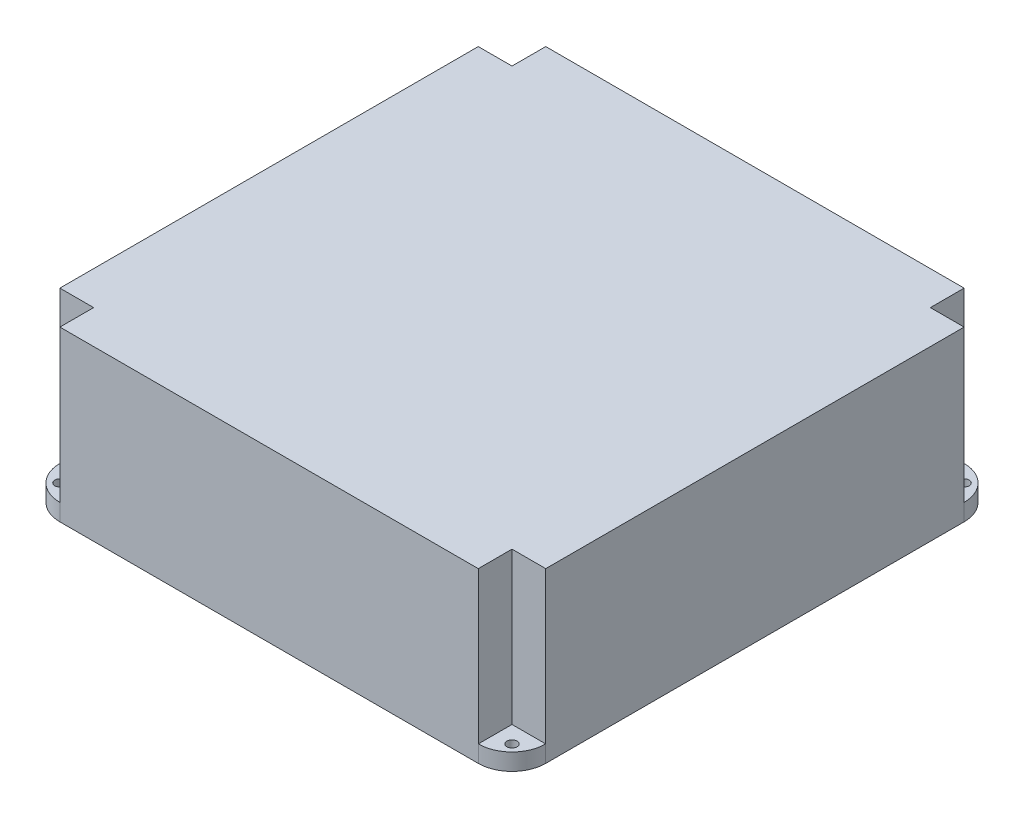
SolidWorks part; units mm, degrees
ref_plane "Front Plane" through (0, 0, 0) normal (0, 0, 1) x (1, 0, 0)
ref_plane "Top Plane" through (0, 0, 0) normal (0, 1, 0) x (1, 0, 0)
ref_plane "Right Plane" through (0, 0, 0) normal (1, 0, 0) x (0, 0, -1)
sketch "Sketch1" plane through (0, 0, 0) normal (0, 1, 0) x (1, 0, 0)
  line L0 (0, 72) -> (0, -72) construction
  line L1 (-62, 72) -> (62, 72)
  line L2 (-72, 62) -> (-72, -62)
  line L3 (-62, -72) -> (62, -72)
  line L5 (-72, 62) -> (-62, 62)
  line L6 (-62, 62) -> (-62, 72)
  line L7 (-72, 0) -> (72, 0) construction
  line L8 (62, 62) -> (62, 72)
  line L9 (72, 62) -> (62, 62)
  line L10 (62, -62) -> (62, -72)
  line L11 (72, -62) -> (62, -62)
  line L12 (-72, -62) -> (-62, -62)
  line L13 (-62, -62) -> (-62, -72)
  line L14 (72, 62) -> (72, -62)
  line L15 (-62, 52) -> (-62, -52)
  line L16 (-62, -52) -> (-52, -52)
  line L17 (-52, -52) -> (-52, -62)
  line L18 (-52, -62) -> (52, -62)
  line L19 (52, -52) -> (52, -62)
  line L20 (62, -52) -> (52, -52)
  line L21 (62, 52) -> (62, -52)
  line L22 (62, 52) -> (52, 52)
  line L23 (52, 52) -> (52, 62)
  line L24 (-52, 62) -> (52, 62)
  line L25 (-52, 52) -> (-52, 62)
  line L26 (-62, 52) -> (-52, 52)
  point P0 (0, 0)
  point P30 (-52, 57)
  point P31 (-57, 52)
  dimension "D1" = 10
  dimension "D2" = 72
  dimension "D3" = 72
  dimension "D4" = 72
  dimension "D5" = 72
  dimension "D6" = 10
  dimension "D7" = 52
  dimension "D8" = 62
  dimension "D9" = 10
  dimension "D10" = 10
  dimension "D11" = 5
  dimension "D12" = 5
  dimension "D13" = 10
extrude "Boss-Extrude1" add sketch "Sketch1" along normal blind 45
sketch "Sketch2" plane through (0, 45, 0) normal (0, 1, 0) x (1, 0, 0)
  line L0 (-62, 72) -> (62, 72)
  line L1 (62, 72) -> (62, 62)
  line L2 (62, 62) -> (72, 62)
  line L3 (72, 62) -> (72, -62)
  line L4 (72, -62) -> (62, -62)
  line L5 (62, -62) -> (62, -72)
  line L6 (62, -72) -> (-62, -72)
  line L7 (-62, -72) -> (-62, -62)
  line L8 (-62, -62) -> (-72, -62)
  line L9 (-72, -62) -> (-72, 62)
  line L10 (-72, 62) -> (-62, 62)
  line L12 (-62, 62) -> (-62, 72)
extrude "Boss-Extrude2" add sketch "Sketch2" along normal blind 5
sketch "Sketch4" plane through (0, 0, 0) normal (0, -1, 0) x (1, 0, 0)
  line L0 (52, 57) -> (52, 52)
  line L1 (52, 62) -> (52, 52) construction
  line L2 (52, 52) -> (57, 52)
  line L3 (52, 52) -> (62, 52) construction
  line L4 (57, 52) -> (57, 57)
  line L5 (57, 57) -> (52, 57)
  line L6 (-67, 15) -> (-67, 0)
  line L7 (-67, 0) -> (-62, 0)
  line L8 (-62, -52) -> (-62, 52) construction
  line L9 (-62, 0) -> (-62, 15)
  line L10 (-62, -52) -> (-62, 52) construction
  line L11 (-62, 15) -> (-67, 15)
  line L12 (52, -52) -> (52, -62) construction
  line L13 (52, -52) -> (52, -57)
  line L14 (52, -57) -> (65.597, -57)
  line L15 (65.597, -57) -> (65.597, -52)
  line L16 (65.597, -52) -> (52, -52)
  dimension "D1" = 5
  dimension "D2" = 13.597
extrude "Cut-Extrude2" cut sketch "Sketch4" against normal up to surface (45 mm away) up to face at (0, 45, 0)
sketch "Sketch5" plane through (0, 0, 0) normal (0, -1, 0) x (1, 0, 0)
  circle A0 centre (11.02, -60.75) radius 5
  dimension "D1" = 10
extrude "Cut-Extrude3" cut sketch "Sketch5" against normal blind 45
sketch "Sketch6" plane through (0, 0, 0) normal (0, -1, 0) x (1, 0, 0)
  circle A0 centre (0, 66.667) radius 1
  circle A1 centre (0, -66.67) radius 1
  dimension "D1" = 2
  dimension "D2" = 2
  dimension "D3" = 66.667
  dimension "D4" = 66.67
extrude "Cut-Extrude4" cut sketch "Sketch6" against normal blind 10
ref_plane "Plane2" through (0, 0, 0) normal (0, -1, 0) x (-1, 0, 0)
sketch "Sketch8" plane through (0, 0, 0) normal (0, -1, 0) x (-1, 0, 0)
  line L0 (62, 62) -> (72, 62) construction
  line L1 (62, 72) -> (62, 62) construction
  line L2 (62, 72) -> (62, 62)
  line L3 (62, 62) -> (72, 62)
  line L4 (0, 0) -> (0, 50000) construction
  line L5 (0, 0) -> (50000, 0) construction
  line L6 (62, -72) -> (62, -62)
  line L7 (62, -62) -> (72, -62)
  line L8 (-62, -62) -> (-72, -62)
  line L9 (-62, -72) -> (-62, -62)
  line L10 (-62, 62) -> (-72, 62)
  line L11 (-62, 72) -> (-62, 62)
  arc A0 (62, 72) -> (72, 62) centre (62, 62) cw
  arc A1 (62, -72) -> (72, -62) centre (62, -62) ccw
  arc A2 (-62, -72) -> (-72, -62) centre (-62, -62) cw
  arc A3 (-62, 72) -> (-72, 62) centre (-62, 62) ccw
extrude "Boss-Extrude3" add sketch "Sketch8" against normal blind 5
sketch "Sketch9" plane through (0, 5, 0) normal (0, 1, 0) x (1, 0, 0)
  line L0 (0, 0) -> (0, 50000) construction
  line L3 (0, 0) -> (50000, 0) construction
  circle A0 centre (-67, -67) radius 1.5
  circle A1 centre (67, -67) radius 1.5
  circle A2 centre (67, 67) radius 1.5
  circle A3 centre (-67, 67) radius 1.5
extrude "Cut-Extrude5" cut sketch "Sketch9" against normal blind 5
